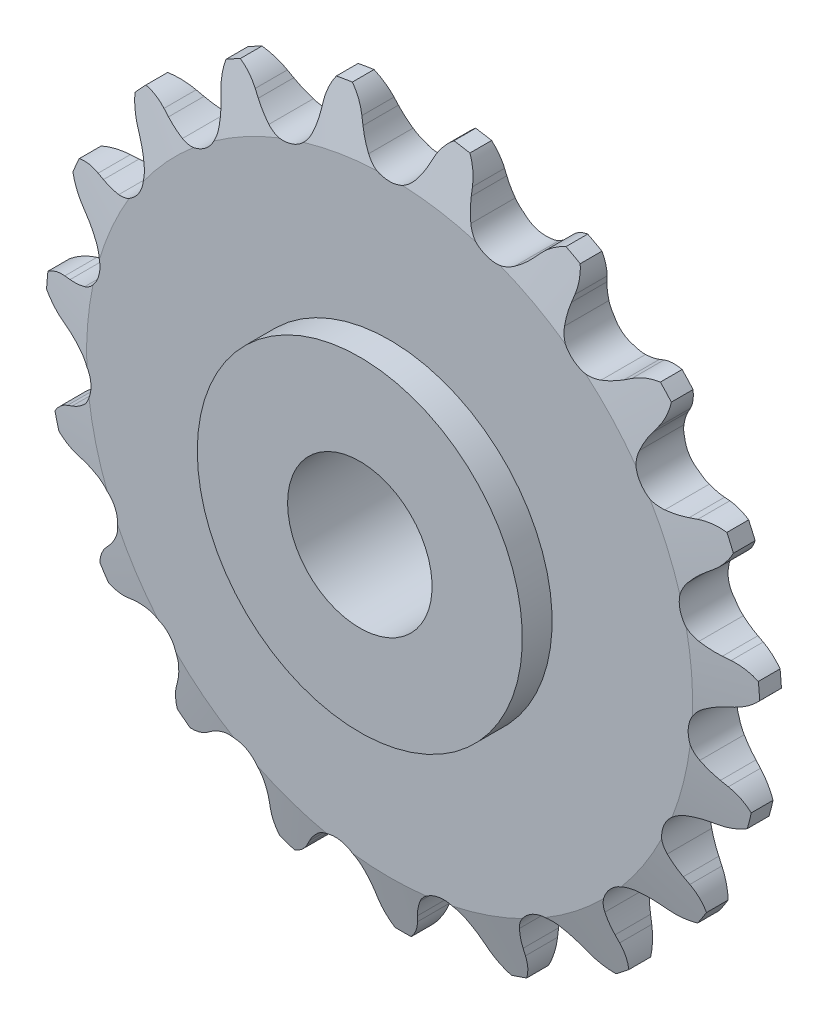
SolidWorks part; units mm, degrees
ref_plane "Front Plane" through (0, 0, 0) normal (0, 0, 1) x (1, 0, 0)
ref_plane "Top Plane" through (0, 0, 0) normal (0, 1, 0) x (1, 0, 0)
ref_plane "Right Plane" through (0, 0, 0) normal (1, 0, 0) x (0, 0, -1)
sketch "Sketch0" plane through (0, 0, 0) normal (0, 0, 1) x (1, 0, 0)
  line L0 (4.7625, -28.5401) -> (0, 0) construction
  line L1 (0, 0) -> (13.7714, -25.4473) construction
  line L2 (0, 0) -> (-4.7625, -28.5401) construction
  line L3 (4.7625, -28.5401) -> (13.7714, -25.4473) construction
  line L4 (4.7625, -28.5401) -> (-4.7625, -28.5401) construction
  line L5 (7.9657, -28.4824) -> (7.6315, -27.9593)
  line L6 (4.7625, -28.5401) -> (0, -29.3348) construction
  line L7 (1.7141, -29.5256) -> (1.8604, -28.9224)
  line L8 (0, -28.5401) -> (0, -31.3976) construction
  line L9 (6.5084, -26.6259) -> (2.0238, -31.5427) construction
  line L10 (0, 0) -> (0, -28.5401) construction
  line L11 (7.6315, -27.9593) -> (2.0238, -31.5427) construction
  line L12 (0, -31.3976) -> (0, -31.999) construction
  line L13 (11.4892, -26.2308) -> (7.9657, -28.4824) construction
  circle A0 centre (0, 0) radius 31.3976 construction
  circle A1 centre (0, 0) radius 28.9347 construction
  arc A2 (-2.6926, -32.7074) -> (13.1668, -30.061) centre (0, 0) ccw
  circle A3 centre (0, 0) radius 31.999 construction
  circle A4 centre (4.7625, -28.5401) radius 2.54 construction
  arc A7 (6.5084, -26.6259) -> (2.4896, -27.2966) centre (4.7625, -28.5401) ccw
  circle A8 centre (4.7625, -28.5401) radius 2.5908 construction
  arc A9 (7.9657, -28.4824) -> (13.1668, -30.061) centre (11.4892, -26.2308) ccw
  arc A10 (7.6315, -27.9593) -> (6.5084, -26.6259) centre (2.0238, -31.5427) ccw
  arc A11 (1.7141, -29.5256) -> (-2.6926, -32.7074) centre (-2.3495, -28.5401) cw
  arc A12 (1.8604, -28.9224) -> (2.4896, -27.2966) centre (8.3278, -30.4907) cw
  dimension "D1" = 2.5908
  dimension "R" = 2.5908
sketch "Sketch1" plane through (0, 0, 0) normal (1, 0, 0) x (0, 0, -1)
  line L0 (-2.1463, 0) -> (2.1463, 0)
  line L1 (-2.1463, 0) -> (-2.1463, 26.6351)
  line L2 (-2.1463, 26.6351) -> (-0.9557, 31.3976)
  line L3 (-0.9557, 31.3976) -> (0.9557, 31.3976)
  line L4 (0.9557, 31.3976) -> (2.1463, 26.6351)
  line L5 (2.1463, 26.6351) -> (2.1463, 0)
  line L7 (0, 31.3976) -> (0, 0) construction
  line L8 (-2.1463, 26.6351) -> (2.1463, 26.6351) construction
  line L9 (0, 31.3976) -> (0, -31.3976) construction
  line L10 (-2.1463, 26.6351) -> (-2.1463, 31.3976) construction
  line L11 (-2.1463, 31.3976) -> (-0.9557, 31.3976) construction
  line L12 (0.9557, 31.3976) -> (2.1463, 31.3976) construction
  line L13 (2.1463, 31.3976) -> (2.1463, 26.6351) construction
revolve "Revolve1" add sketch "Sketch1" angle 360 mid plane about L0
extrude "Cut-Extrude1" cut sketch "Sketch0" against normal through all and the other way through all
pattern_circular "CirPattern1" count 19 over 360 about axis through (0, 0, 0) along (0, 0, 1) of "Cut-Extrude1"
sketch "Sketch2" plane through (0, 0, 0) normal (0, 0, 1) x (1, 0, 0)
  circle A0 centre (0, 0) radius 6.35 construction
  circle A1 centre (0, 0) radius 14.2875
  circle A2 centre (0, 0) radius 31.369 construction
  dimension "Bore" = 12.7
  dimension "Hub Dia." = 28.575
  dimension "OD" = 62.738
extrude "Boss-Extrude1" add sketch "Sketch2" along normal mid plane 9.525
sketch "Sketch3" plane through (0, 0, 0) normal (0, 0, 1) x (1, 0, 0)
  circle A0 centre (0, 0) radius 6.35 construction
  circle A1 centre (0, 0) radius 6.35
extrude "Cut-Extrude2" cut sketch "Sketch3" along normal through all and the other way through all
equation "\"360/N@Sketch0\" = 360/\"Teeth@CirPattern1\""
equation "\"Ds@Sketch0\" = 1.005 * \"Dr@Sketch0\" + 0.003"
equation "\"R@Sketch0\" = 1/2 * \"Ds@Sketch0\""
equation "\"A@Sketch0\" = 35 +  ( 60 / \"Teeth@CirPattern1\" ) "
equation "\"B@Sketch0\" = 18 -  ( 56 / \"Teeth@CirPattern1\" )"
equation "\"ac@Sketch0\" = 0.8 * \"Dr@Sketch0\""
equation "\"ab@Sketch0\" = 1.4 * \"Dr@Sketch0\""
equation "\"J@Sketch0\" = 0.3 * \"Pitch@Sketch0\""
equation "\"h@Sketch1\" = \"Pitch@Sketch0\" / 2"
equation "\"g@Sketch1\" = \"h@Sketch1\" / 4"
